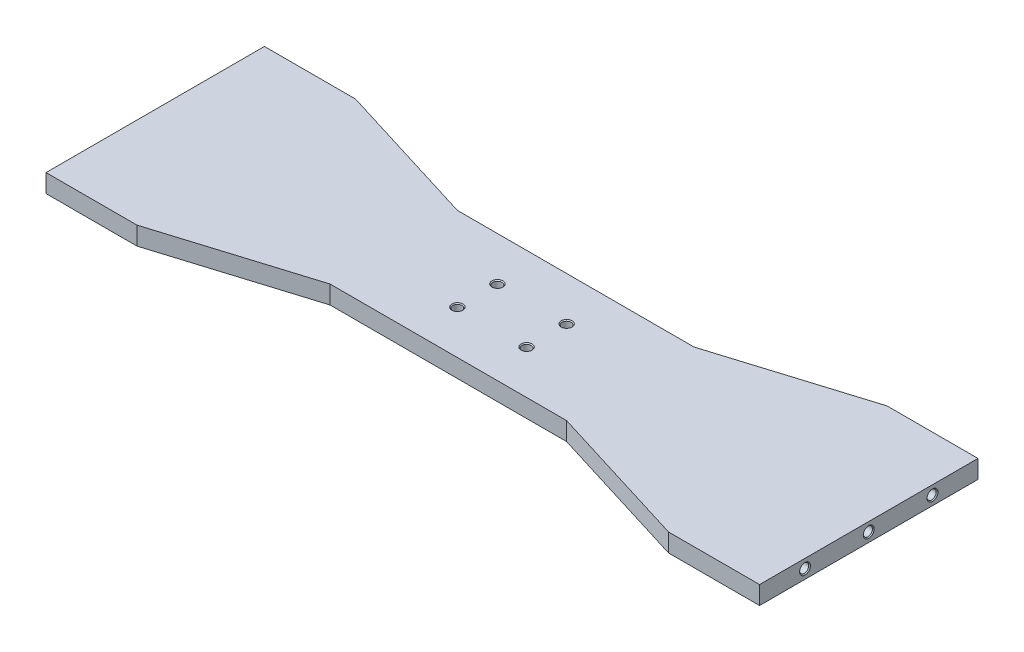
SolidWorks part; units mm, degrees
ref_plane "Alzado" through (0, 0, 0) normal (0, 0, 1) x (1, 0, 0)
ref_plane "Planta" through (0, 0, 0) normal (0, 1, 0) x (1, 0, 0)
ref_plane "Vista lateral" through (0, 0, 0) normal (1, 0, 0) x (0, 0, -1)
sketch "Croquis1" plane through (0, 0, 0) normal (0, 1, 0) x (1, 0, 0)
  line L1 (0, 0) -> (392, 0)
  line L2 (0, 0) -> (0, 120)
  line L3 (0, 120) -> (392, 120)
  line L4 (392, 0) -> (392, 120)
  dimension "D1" = 392
  dimension "D2" = 120
extrude "Saliente-Extruir1" add sketch "Croquis1" against normal blind 10
sketch "Croquis2" plane through (0, -10, 0) normal (0, -1, 0) x (1, 0, 0)
  line L0 (0, -60) -> (392, -60) construction
  line L1 (0, -120) -> (0, 0) construction
  line L2 (392, 0) -> (392, -120) construction
  line L3 (177, -49) -> (177, -71) construction
  line L4 (392, -120) -> (0, -120) construction
  line L5 (196, -120) -> (196, 0) construction
  line L6 (0, 0) -> (392, 0) construction
  line L7 (177, -71) -> (215, -71) construction
  line L8 (215, -71) -> (215, -49) construction
  line L9 (215, -49) -> (177, -49) construction
  circle A0 centre (177, -49) radius 2.5
  circle A1 centre (177, -71) radius 2.5
  circle A2 centre (215, -49) radius 2.5
  circle A3 centre (215, -71) radius 2.5
  dimension "D5" = 5
  dimension "D1" = 19
  dimension "D2" = 19
  dimension "D3" = 11
  dimension "D4" = 11
extrude "Cortar-Extruir1" cut sketch "Croquis2" against normal through all
chamfer "Chaflán1" distance 0.5 angle 45 8 edges at (177, 0, -51.5) (177, 0, -73.5) (215, 0, -73.5) (215, 0, -51.5) (215, -10, -51.5) (215, -10, -73.5) (177, -10, -73.5) (177, -10, -51.5)
sketch "Croquis3" plane through (392, 0, 0) normal (1, 0, 0) x (0, 0, -1)
  line L0 (0, -5) -> (120, -5) construction
  line L1 (0, -10) -> (0, 0) construction
  line L2 (120, -10) -> (120, 0) construction
  line L3 (60, -10) -> (60, 0) construction
  line L4 (0, -10) -> (120, -10) construction
  line L5 (0, 0) -> (120, 0) construction
  circle A0 centre (25, -5) radius 2.5
  circle A1 centre (60, -5) radius 2.5
  circle A2 centre (95, -5) radius 2.5
  dimension "D1" = 5
  dimension "D3" = 35
  dimension "50" = 35
extrude "Cortar-Extruir2" cut sketch "Croquis3" against normal blind 30
sketch "Croquis4" plane through (0, 0, 0) normal (-1, 0, 0) x (0, 0, 1)
  line L0 (0, -5) -> (-120, -5) construction
  line L1 (0, -10) -> (0, 0) construction
  line L2 (-120, -10) -> (-120, 0) construction
  line L3 (-60, 0) -> (-60, -10) construction
  line L4 (-120, 0) -> (0, 0) construction
  line L5 (-120, -10) -> (0, -10) construction
  circle A0 centre (-25, -5) radius 2.5
  circle A1 centre (-60, -5) radius 2.5
  circle A2 centre (-95, -5) radius 2.5
  dimension "D1" = 5
  dimension "D2" = 35
  dimension "D3" = 35
extrude "Cortar-Extruir3" cut sketch "Croquis4" against normal blind 30
chamfer "Chaflán2" distance 0.5 angle 45 6 edges at (392, -5, -97.5) (392, -5, -62.5) (392, -5, -27.5) (0, -5, -92.5) (0, -5, -57.5) (0, -5, -22.5)
sketch "Croquis5" plane through (0, -10, 0) normal (0, -1, 0) x (1, 0, 0)
  line L0 (50, 0) -> (131, -25)
  line L1 (0, 0) -> (392, 0) construction
  line L2 (131, -25) -> (261, -25)
  line L3 (261, -25) -> (342, 0)
  line L4 (0, -60) -> (392, -60) construction
  line L5 (0, -120) -> (0, 0) construction
  line L6 (392, 0) -> (392, -120) construction
  line L7 (342, 0) -> (50, 0)
  line L8 (261, -95) -> (342, -120)
  line L9 (131, -95) -> (261, -95)
  line L10 (50, -120) -> (131, -95)
  line L11 (342, -120) -> (50, -120)
  dimension "D1" = 50
  dimension "D2" = 50
  dimension "D3" = 25
  dimension "D4" = 81
  dimension "D5" = 81
  dimension "D6" = 130
extrude "Cortar-Extruir4" cut sketch "Croquis5" against normal through all
